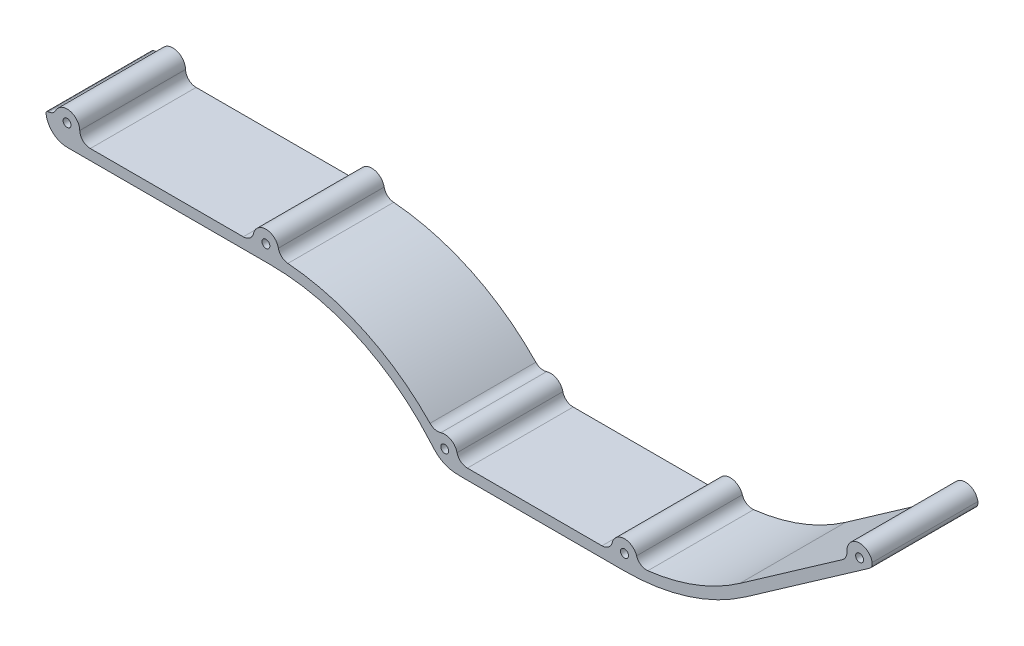
SolidWorks part; units mm, degrees
ref_plane "Front Plane" through (0, 0, 0) normal (0, 0, 1) x (1, 0, 0)
ref_plane "Top Plane" through (0, 0, 0) normal (0, 1, 0) x (1, 0, 0)
ref_plane "Right Plane" through (0, 0, 0) normal (1, 0, 0) x (0, 0, -1)
sketch "Sketch1" plane through (0, 0, 0) normal (0, 0, 1) x (1, 0, 0)
  line L2 (-535.3014, 236.0765) -> (-441.59, 236.0765)
  line L4 (-348.1182, 194.3651) -> (-271.4891, 194.3651)
  line L5 (-214.1314, 212.4499) -> (-155.6765, 253.3805)
  line L9 (-534.9592, 241.0765) -> (-441.59, 241.0765) construction
  line L10 (-534.9592, 241.0765) -> (-439.0626, 241.0765) construction
  line L11 (-347.0262, 199.3651) -> (-271.4891, 199.3651) construction
  line L13 (-363.2756, 201.317) -> (-348.1182, 194.3651) construction
  line L14 (-543.9964, 246.1575) -> (-543.5974, 246.1911)
  line L15 (-523.9636, 241.0765) -> (-451.67, 241.0765)
  line L16 (-523.9636, 241.0765) -> (-451.67, 241.0765)
  line L17 (-345.7493, 199.3651) -> (-282.1286, 199.3651)
  line L18 (-216.9993, 216.5457) -> (-153.8971, 260.7303) construction
  line L19 (-216.9993, 216.5457) -> (-168.4643, 250.5303)
  line L20 (-360.2113, 205.4124) -> (-347.0262, 199.3651) construction
  line L23 (-214.1314, 212.4499) -> (-151.0292, 256.6346) construction
  line L26 (-214.1314, 212.4499) -> (-146.3556, 259.9071)
  line L27 (-139.9592, 272.1944) -> (-139.9592, 295.693)
  line L28 (-148.5675, 305.5957) -> (-289.2633, 325.3692)
  line L29 (-294.9592, 320.4179) -> (-294.9592, 289.1697)
  line L30 (-294.9592, 286.1697) -> (-319.9592, 286.1697)
  line L31 (-319.9592, 289.1697) -> (-319.9592, 321.3651)
  line L32 (-324.9592, 326.3651) -> (-367.3265, 326.3651)
  line L33 (-401.5285, 320.3344) -> (-419.9592, 313.6262)
  line L34 (-419.9592, 313.6262) -> (-532.7101, 266.226)
  line L35 (-544.9592, 247.789) -> (-544.9592, 246.0765)
  line L36 (-534.9592, 236.0765) -> (-439.0626, 236.0765)
  line L37 (-348.1182, 194.3651) -> (-271.4891, 194.3651)
  line L54 (-534.9592, 236.0765) -> (-439.0626, 236.0765)
  line L55 (-348.1182, 194.3651) -> (-271.4891, 194.3651)
  arc A2 (-271.4891, 194.3651) -> (-214.1314, 212.4499) centre (-271.4891, 294.3651) ccw
  arc A6 (-350.6185, 203.229) -> (-358.2818, 207.583) centre (-356.4616, 201.8657) ccw
  circle A7 centre (-356.4616, 201.8657) radius 1.875
  arc A9 (-360.2113, 205.4124) -> (-439.0626, 241.0765) centre (-439.0626, 136.0765) ccw construction
  arc A11 (-265.7834, 203.4282) -> (-277.2924, 203.0955) centre (-271.4891, 201.572) ccw
  circle A12 centre (-271.4891, 201.572) radius 1.875
  arc A17 (-435.0807, 244.7334) -> (-446.8034, 244.9294) centre (-440.9634, 243.5529) ccw
  circle A18 centre (-440.9634, 243.5529) radius 1.875
  arc A19 (-154.4393, 256.3385) -> (-166.3427, 254.9494) centre (-160.3552, 255.3374) ccw
  circle A20 centre (-160.3552, 255.3374) radius 1.875
  arc A21 (-271.4891, 199.3651) -> (-216.9993, 216.5457) centre (-271.4891, 294.3651) ccw construction
  arc A22 (-363.4016, 208.8805) -> (-430.5823, 240.7335) centre (-439.0626, 136.0765) ccw
  arc A23 (-260.4476, 200.009) -> (-216.9993, 216.5457) centre (-271.4891, 294.3651) ccw
  arc A24 (-543.5974, 246.1911) -> (-540.3434, 248.4118) centre (-543.9328, 250.177) ccw
  arc A25 (-528.9616, 245.9345) -> (-523.9636, 241.0765) centre (-523.9636, 246.0765) ccw
  arc A26 (-446.8034, 244.9294) -> (-451.67, 241.0765) centre (-451.67, 246.0765) cw
  arc A27 (-430.5823, 240.7335) -> (-435.0807, 244.7334) centre (-430.1784, 245.7172) cw
  arc A31 (-358.2818, 207.583) -> (-363.4016, 208.8805) centre (-359.7987, 212.3473) cw
  arc A32 (-350.6185, 203.229) -> (-345.7493, 199.3651) centre (-345.7493, 204.3651) ccw
  arc A33 (-277.2924, 203.0955) -> (-282.1286, 199.3651) centre (-282.1286, 204.3651) cw
  arc A34 (-265.7834, 203.4282) -> (-260.4476, 200.009) centre (-261.0287, 204.9751) ccw
  arc A35 (-166.3427, 254.9494) -> (-168.4643, 250.5303) centre (-171.3322, 254.626) cw
  arc A36 (-146.3556, 259.9071) -> (-139.9592, 272.1944) centre (-154.9592, 272.1944) ccw
  arc A37 (-139.9592, 295.693) -> (-148.5675, 305.5957) centre (-149.9592, 295.693) ccw
  arc A38 (-289.2633, 325.3692) -> (-294.9592, 320.4179) centre (-289.9592, 320.4179) ccw
  arc A39 (-294.9592, 286.1697) -> (-294.9592, 289.1697) centre (-294.9592, 287.6697) ccw
  arc A40 (-319.9592, 289.1697) -> (-319.9592, 286.1697) centre (-319.9592, 287.6697) ccw
  arc A41 (-319.9592, 321.3651) -> (-324.9592, 326.3651) centre (-324.9592, 321.3651) ccw
  arc A42 (-367.3265, 326.3651) -> (-401.5285, 320.3344) centre (-367.3265, 226.3651) ccw
  arc A43 (-532.7101, 266.226) -> (-544.9592, 247.789) centre (-524.9592, 247.789) ccw
  arc A44 (-544.9592, 246.0765) -> (-534.9592, 236.0765) centre (-534.9592, 246.0765) ccw
  arc A45 (-363.2756, 201.317) -> (-439.0626, 236.0765) centre (-439.0626, 136.0765) ccw
  arc A46 (-271.4891, 194.3651) -> (-214.1314, 212.4499) centre (-271.4891, 294.3651) ccw
  arc A55 (-544.9073, 245.0593) -> (-534.9592, 236.0765) centre (-534.9592, 246.0765) ccw
  arc A56 (-363.2756, 201.317) -> (-439.0626, 236.0765) centre (-439.0626, 136.0765) ccw
  arc A57 (-271.4891, 194.3651) -> (-214.1314, 212.4499) centre (-271.4891, 294.3651) ccw
  arc A58 (-154.4393, 256.3385) -> (-155.6765, 253.3805) centre (-157.3973, 255.8379) cw
  arc A59 (-543.9964, 246.1575) -> (-544.9073, 245.0593) centre (-543.9125, 245.1611) ccw
  circle A62 centre (-534.9592, 246.0765) radius 1.875
  arc A63 (-528.9616, 245.9345) -> (-540.3434, 248.4118) centre (-534.9592, 245.7641) ccw
  arc A64 (-539.9768, 246.4958) -> (-534.9592, 241.0765) centre (-533.998, 246.999) ccw construction
  arc A66 (-544.9592, 246.0765) -> (-535.3014, 236.0765) centre (-533.998, 246.999) ccw construction
  spline S1 degree 2 poles (-3548.799, 4055.0006) (-389.9233, 230.0513) (-361.8332, 199.6737) (-361.0416, 198.8177) (-360.2763, 198.1384) (-358.5238, 196.583) (-356.6619, 195.7295) (-354.8004, 194.8761) (-352.4847, 194.5695) (-351.4883, 194.4375) (-350.3053, 194.3933) (-286.8622, 192.0194) (4647.9378, 390.0082) knots -8.621298 -8.621298 -8.621298 0.125 0.125 0.25 0.25 0.5 0.5 0.75 0.75 0.875 0.875 11.425509 11.425509 11.425509 only from (-363.2756, 201.317) to (-348.1182, 194.3651)
  spline S2 degree 2 poles (-363.2756, 201.317) (-362.2346, 200.1078) (-361.8332, 199.6737) (-361.0416, 198.8177) (-360.2763, 198.1384) (-358.5238, 196.583) (-356.6619, 195.7295) (-354.8004, 194.8761) (-352.4847, 194.5695) (-351.4883, 194.4375) (-350.3053, 194.3933) (-349.5536, 194.3651) (-348.1182, 194.3651) knots 0 0 0 0.125 0.125 0.25 0.25 0.5 0.5 0.75 0.75 0.875 0.875 1 1 1
  dimension "D4" = 3.75
  dimension "D3" = 12
  dimension "D5" = 12
  dimension "D6" = 3.75
  dimension "D7" = 3.75
  dimension "D8" = 12
  dimension "D9" = 12
  dimension "D2" = 12
  dimension "D11" = 3.75
  dimension "D12" = 3.75
  dimension "D13" = 4
  dimension "D14" = 5
  dimension "D15" = 5
  dimension "D16" = 5
  dimension "D17" = 5
  dimension "D18" = 5
  dimension "D19" = 5
  dimension "D20" = 5
  dimension "D21" = 5
  dimension "D22" = 3
  dimension "D23" = 1
  dimension "D10" = 0
extrude "Boss-Extrude1" add sketch "Sketch1" along normal blind 50
sketch "Sketch3" plane through (0, 0, 50) normal (0, 0, 1) x (1, 0, 0)
  circle A0 centre (-271.4891, 201.572) radius 1.5
  dimension "D1" = 3
